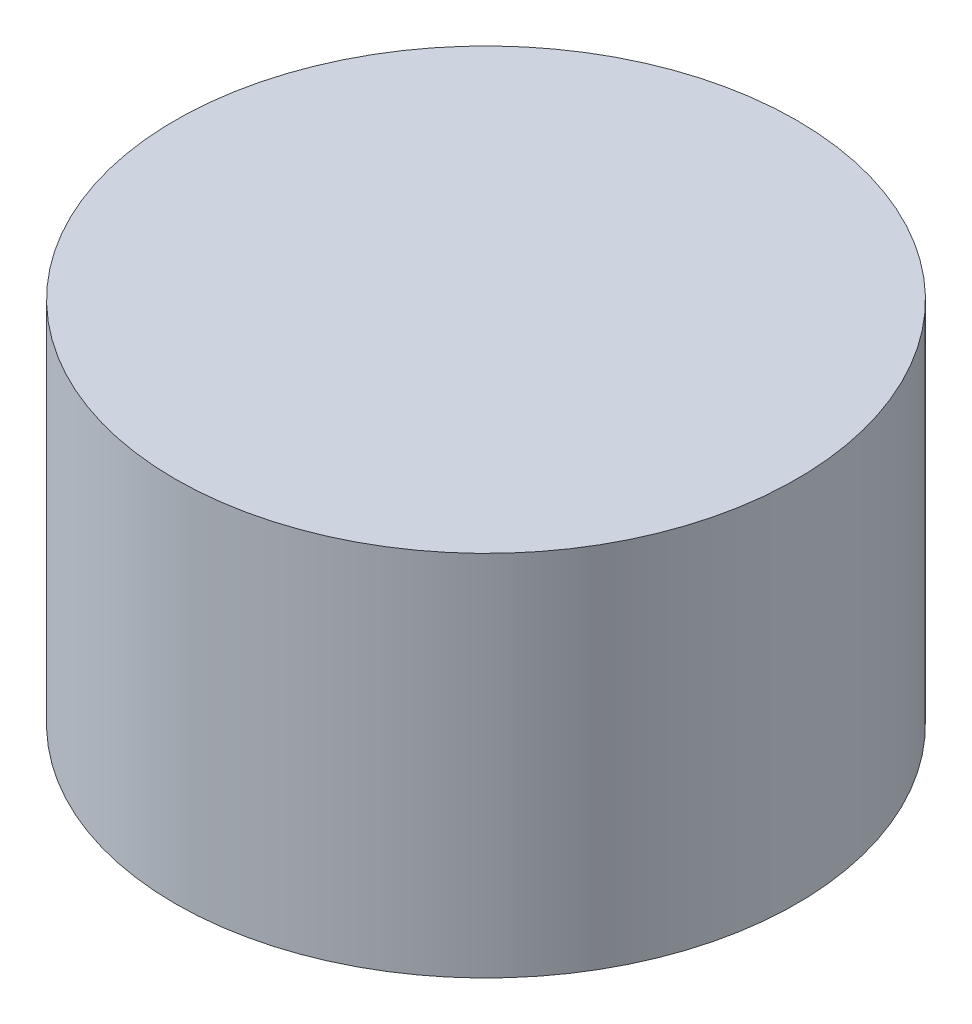
SolidWorks part; units mm, degrees
ref_plane "Front Plane" through (0, 0, 0) normal (0, 0, 1) x (1, 0, 0)
ref_plane "Top Plane" through (0, 0, 0) normal (0, 1, 0) x (1, 0, 0)
ref_plane "Right Plane" through (0, 0, 0) normal (1, 0, 0) x (0, 0, -1)
sketch "Sketch1" plane through (0, 0, 0) normal (0, 1, 0) x (1, 0, 0)
  circle A0 centre (-31.5739, 9.7515) radius 8.45
  dimension "D1" = 16.9
extrude "Boss-Extrude1" add sketch "Sketch1" along normal blind 10
